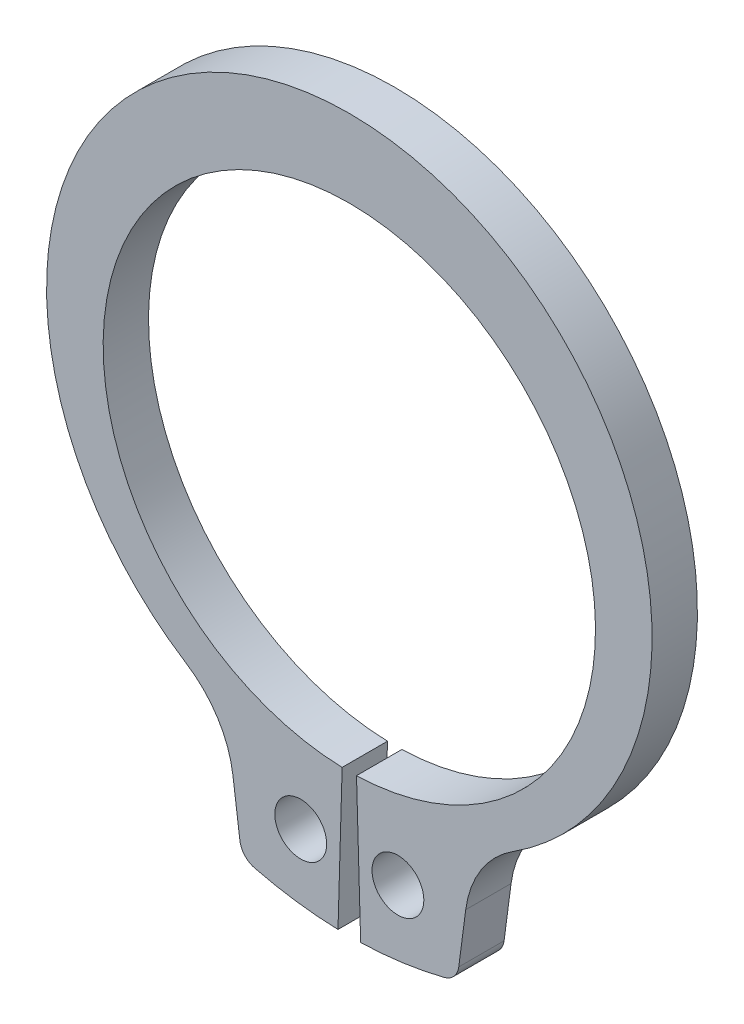
SolidWorks part; units mm, degrees
ref_plane "Plane1" through (0, 0, 0) normal (0, 0, 1) x (1, 0, 0)
ref_plane "Plane2" through (0, 0, 0) normal (0, 1, 0) x (1, 0, 0)
ref_plane "Plane3" through (0, 0, 0) normal (1, 0, 0) x (0, 0, -1)
sketch "Clipboard" plane through (0, 0, 0) normal (0, 0, 1) x (1, 0, 0)
  line L0 (0, 0) -> (3, 0)
  line L1 (0, 0) -> (0, 1.5)
  line L2 (0, 0) -> (0, -5.5)
  circle A0 centre (0, 0) radius 1
  circle A1 centre (0, 0) radius 10
  dimension "HoleDia" = 2
  dimension "ShaftDia" = 20
  dimension "LargeSection" = 3
  dimension "SmallSection" = 1.5
  dimension "LugSection" = 5.5
sketch "BodySke" plane through (0, 0, 0) normal (0, 0, 1) x (1, 0, 0)
  line L0 (-1.5431, 0) -> (1.5431, 0) construction
  line L1 (0, 0) -> (0, 12.5) construction
  line L2 (0.2771, -9.496) -> (0.4375, -14.9936)
  line L3 (-0.2771, -9.496) -> (-0.4375, -14.9936)
  line L4 (0, 0) -> (8.4554, -12.3898) construction
  line L5 (0, 0) -> (-8.4554, -12.3898) construction
  line L7 (4.4919, -11.868) -> (4.2222, -13.9168)
  line L8 (-4.4919, -11.868) -> (-4.2222, -13.9168)
  circle A0 centre (0, 0) radius 9.5 construction
  arc A1 (0.2771, -9.496) -> (-0.2771, -9.496) centre (0, 0) ccw
  arc A2 (6.2006, -9.0858) -> (-6.2006, -9.0858) centre (0, 0.8165) ccw construction
  arc A3 (0.4375, -14.9936) -> (3.6617, -14.5462) centre (0, 0) ccw
  arc A4 (6.2998, -9.023) -> (4.4919, -11.868) centre (8.4554, -12.3898) ccw
  arc A5 (-4.4919, -11.868) -> (-6.2998, -9.023) centre (-8.4554, -12.3898) ccw
  arc A6 (-3.6617, -14.5462) -> (-0.4375, -14.9936) centre (0, 0) ccw
  arc A7 (6.2998, -9.023) -> (-6.2998, -9.023) centre (0, 0.8165) ccw
  arc A8 (-4.5201, -11.6541) -> (4.5201, -11.6541) centre (0, 0) ccw construction
  circle A9 centre (1.875, -12.3586) radius 1
  circle A10 centre (-1.875, -12.3586) radius 1
  arc A11 (4.2222, -13.9168) -> (3.6617, -14.5462) centre (3.4786, -13.8189) cw
  arc A12 (-4.2222, -13.9168) -> (-3.6617, -14.5462) centre (-3.4786, -13.8189) ccw
  point P28 (4.1569, -14.4125)
  point P31 (-4.1569, -14.4125)
  dimension "HoleDia" = 2
  dimension "GrooveDia" = 19
  dimension "LugRad" = 15
  dimension "HoleOffsetRad" = 12.5
  dimension "D3" = 0.75
  dimension "LargeRad" = 12.5
  dimension "SmallRad" = 11
  dimension "SmallAngle" = 68.623
  dimension "D2" = 15
  dimension "HoleSpacing" = 3.75
  dimension "Gap" = 0.875
extrude "Body" add sketch "BodySke" against normal blind 1.75
sketch "NotSke" plane through (0, 0, 0) normal (0, 0, 1) x (1, 0, 0)
  line L0 (1.875, -11.3586) -> (1.875, -13.3586)
  line L1 (1.875, -13.3586) -> (-1.875, -13.3586)
  line L2 (-1.875, -13.3586) -> (-1.875, -11.3586)
  line L3 (-1.875, -11.3586) -> (1.875, -11.3586)
  circle A0 centre (1.875, -12.3586) radius 1 construction
  circle A1 centre (-1.875, -12.3586) radius 1 construction
extrude "Notch" [suppressed] cut sketch "NotSke" against normal through all
sketch "UnlSke" plane through (0, 0, 0) normal (0, 0, 1) x (1, 0, 0)
  line L0 (-3.4292, -14.6028) -> (-2.1718, -9.2484)
  line L1 (3.4292, -14.6028) -> (2.1718, -9.2484)
  arc A0 (2.1718, -9.2484) -> (-2.1718, -9.2484) centre (0, 0) ccw
  arc A1 (3.4292, -14.6028) -> (-3.4292, -14.6028) centre (0, 0) ccw
  arc A2 (0.4375, -14.9936) -> (3.6617, -14.5462) centre (0, 0) ccw construction
  arc A3 (0.2771, -9.496) -> (-0.2771, -9.496) centre (0, 0) ccw construction
  circle A4 centre (-1.875, -12.3586) radius 1 construction
  circle A5 centre (1.875, -12.3586) radius 1 construction
extrude "Unlug" [suppressed] add sketch "UnlSke" against normal through all
equation "' \"ShaftDia@Clipboard\" = 15"
equation "' \"Thickness@Body\" = 1.5"
equation "' \"GrooveDia@BodySke\" = 14.3"
equation "' \"LugSection@Clipboard\" = 4.8"
equation "' \"LargeSection@Clipboard\" = 2.4"
equation "' \"HoleDia@Clipboard\" = 2.0"
equation "' \"ShaftDia@Clipboard\" = 50"
equation "' \"Thickness@Body\" = 3"
equation "' \"GrooveDia@BodySke\" = 47"
equation "' \"LugSection@Clipboard\" = 8"
equation "' \"LargeSection@Clipboard\" = 5.1"
equation "' \"HoleDia@Clipboard\" = 2.5"
equation "\"SmallSection@Clipboard\" = \"LargeSection@Clipboard\" * 0.5"
equation "\"Gap@BodySke\" =  \"Thickness@Body\" / 2"
equation "\"LargeRad@BodySke\" =  \"GrooveDia@BodySke\" / 2 +  \"LargeSection@Clipboard\""
equation "\"SmallRad@BodySke\" =  \"GrooveDia@BodySke\" / 2 +  \"SmallSection@Clipboard\""
equation "\"LugRad@BodySke\" = \"GrooveDia@BodySke\" / 2 + \"LugSection@Clipboard\""
equation "\"HoleOffsetRad@BodySke\" = (  \"ShaftDia@Clipboard\" / 2 + \"LugRad@BodySke\" ) / 2"
equation "\"HoleSpacing@BodySke\" = \"Gap@BodySke\"  * 2 +  \"HoleDia@Clipboard\""
equation "\"HoleDia@BodySke\" =  \"HoleDia@Clipboard\""
equation "\"SmallAngle@BodySke\" = atn(\"HoleSpacing@BodySke\" / 2 / sqr(\"HoleOffsetRad@BodySke\"  * \"HoleOffsetRad@BodySke\" - (\"HoleSpacing@BodySke\" / 2) * (\"HoleSpacing@BodySke\" / 2) ))  * 7 *  (\"LargeRad@BodySke\" / \"SmallRad@BodySke\")* ( 180 / 3.141593)"
